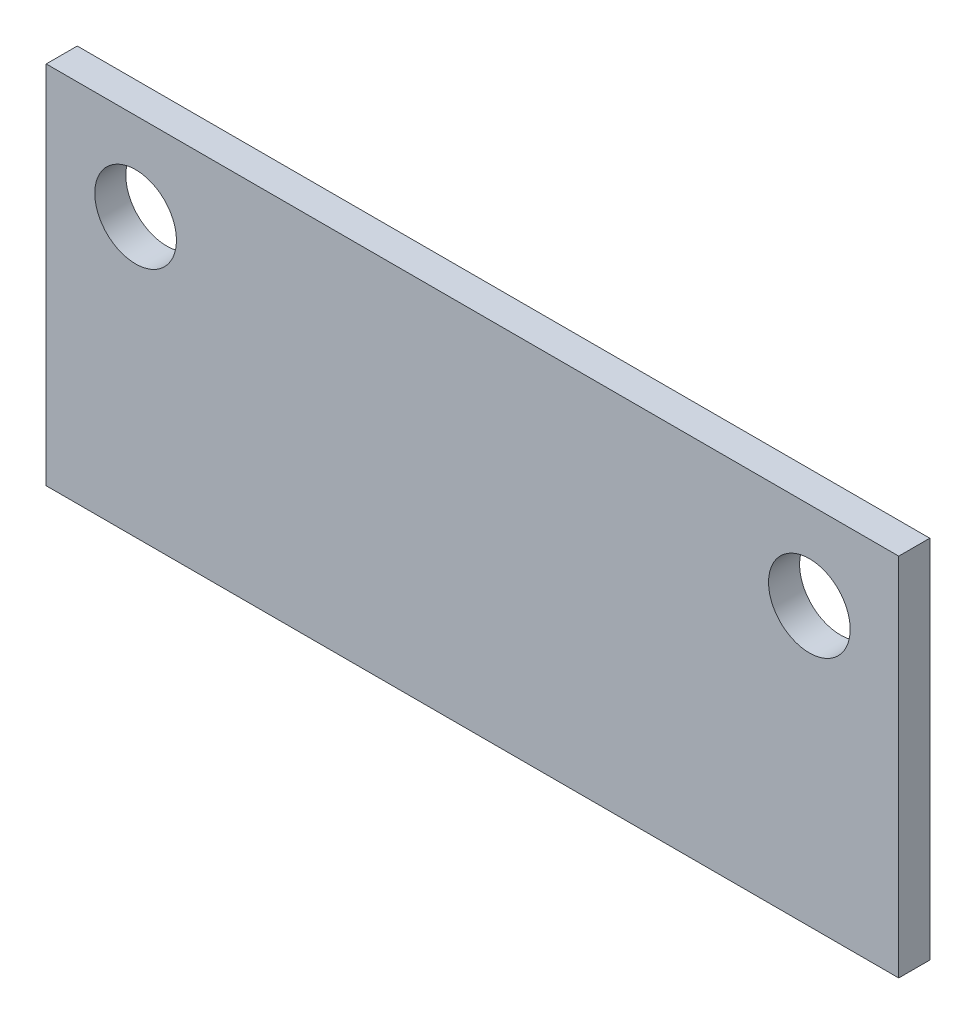
SolidWorks part; units mm, degrees
ref_plane "Front Plane" through (0, 0, 0) normal (0, 0, 1) x (1, 0, 0)
ref_plane "Top Plane" through (0, 0, 0) normal (0, 1, 0) x (1, 0, 0)
ref_plane "Right Plane" through (0, 0, 0) normal (1, 0, 0) x (0, 0, -1)
sketch "Sketch1" plane through (0, 0, 0) normal (0, 0, 1) x (1, 0, 0)
  line L0 (13.2572, 11.3633) -> (13.2572, -8.5445) construction
  line L1 (0, 0) -> (26.5144, 0)
  line L2 (0, 0) -> (0, 11.3633)
  line L3 (0, 11.3633) -> (26.5144, 11.3633)
  line L4 (26.5144, 0) -> (26.5144, 11.3633)
  circle A0 centre (2.7797, 8.636) radius 1.27
  circle A1 centre (23.7347, 8.636) radius 1.27
  dimension "D1" = 20.955
  dimension "D2" = 10.4775
  dimension "D3" = 8.636
  dimension "D4" = 8.636
extrude "Boss-Extrude1" add sketch "Sketch1" along normal blind 0.9652
